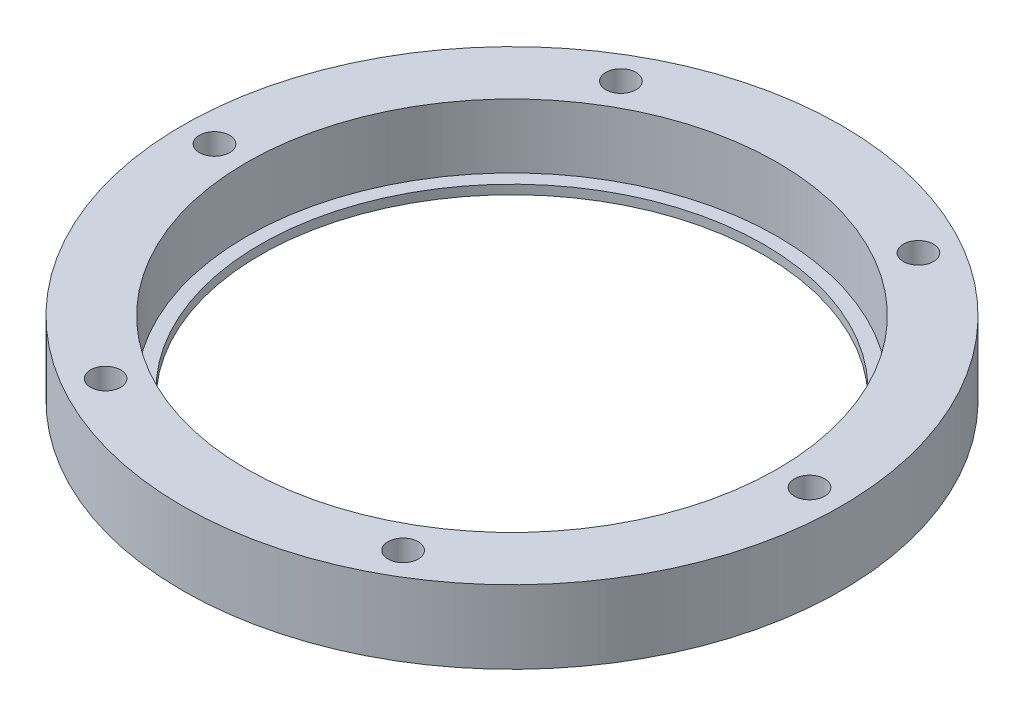
SolidWorks part; units mm, degrees
material "6061 合金"
ref_plane "前视基准面" through (0, 0, 0) normal (0, 0, 1) x (1, 0, 0)
ref_plane "上视基准面" through (0, 0, 0) normal (0, 1, 0) x (1, 0, 0)
ref_plane "右视基准面" through (0, 0, 0) normal (1, 0, 0) x (0, 0, -1)
sketch "草图2" plane through (0, 0, 0) normal (0, 1, 0) x (1, 0, 0)
  circle A0 centre (0, 0) radius 36
  circle A1 centre (0, 0) radius 29
  dimension "D1" = 7
  dimension "D2" = 58
extrude "凸台-拉伸1" add sketch "草图2" along normal blind 7
sketch "草图3" plane through (0, 0, 0) normal (0, -1, 0) x (1, 0, 0)
  circle A0 centre (0, 0) radius 27.5
  circle A1 centre (0, 0) radius 36
  circle A2 centre (0, 0) radius 36
  circle A3 centre (0, 0) radius 29 construction
  dimension "D2" = 1.5
  dimension "D1" = 0
extrude "凸台-拉伸2" add sketch "草图3" along normal blind 1
hole_wizard "M4 螺纹孔1" positions "草图4" profile "草图5" tap size "M4" standard "GB" end condition through all
sketch "草图4" plane through (0, 7, 0) normal (0, 1, 0) x (1, 0, 0)
  circle A0 centre (0, 0) radius 32.5 construction
  circle A1 centre (0, 0) radius 36 construction
  point P0 (-16.25, 28.1458)
  point P26 (16.25, 28.1458)
  point P27 (32.5, 0)
  point P28 (16.25, -28.1458)
  point P29 (-16.25, -28.1458)
  point P30 (-32.5, 0)
  point P32 (28.8692, 14.9272)
  point P33 (28.0193, -16.4673)
  point P34 (0, 0)
  dimension "D1" = 3.5
  dimension "D2" = 6
sketch "草图5" plane through (-16.25, 7, -28.1458) normal (1, 0, 0) x (0, 0, 1)
  line L0 (0, 0) -> (0, 8)
  line L1 (0, 8) -> (1.65, 8)
  line L2 (1.65, 8) -> (1.65, 0)
  line L5 (1.65, 0) -> (0, 0)
  line L11 (0, -6.35) -> (0, 107.95) construction
  dimension "通孔螺纹孔钻头直径" = 3.3
  dimension "通孔螺纹孔钻头深度" = 8
cosmetic thread "孔螺蚊线1" parameters "D1"=12, "D2"=4.3
cosmetic thread "孔螺蚊线2" parameters "D1"=12, "D2"=4.3
cosmetic thread "孔螺蚊线3" parameters "D1"=12, "D2"=4.3
cosmetic thread "孔螺蚊线4" parameters "D1"=12, "D2"=4.3
cosmetic thread "孔螺蚊线5" parameters "D1"=12, "D2"=4.3
cosmetic thread "孔螺蚊线6" parameters "D1"=12, "D2"=4.3
